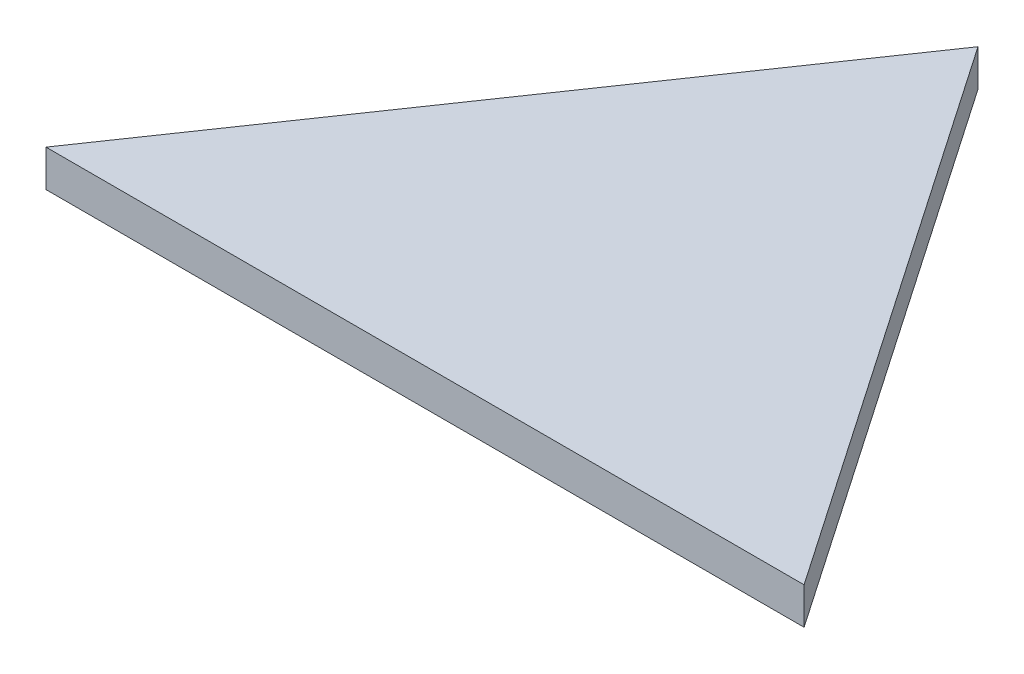
SolidWorks part; units mm, degrees
ref_plane "Front Plane" through (0, 0, 0) normal (0, 0, 1) x (1, 0, 0)
ref_plane "Top Plane" through (0, 0, 0) normal (0, 1, 0) x (1, 0, 0)
ref_plane "Right Plane" through (0, 0, 0) normal (1, 0, 0) x (0, 0, -1)
sketch "Sketch1" plane through (0, 0, 0) normal (0, 1, 0) x (1, 0, 0)
  line L0 (0, 0) -> (1854.0563, 0)
  line L1 (1854.0563, 0) -> (927.0281, 1352.3709)
  line L2 (927.0281, 1352.3709) -> (0, 0)
  dimension "D1" = 1639.6
  dimension "D3" = 68.86
extrude "Boss-Extrude1" add sketch "Sketch1" along normal blind 90
chamfer "Chamfer1" [suppressed] distance 60 angle 11
equation "\"D1@Boss-Extrude1\"=\"thicknes@Geodome.Assembly\""
equation "\"thickne\"=60"
equation "\"D1@Chamfer1\"=\"thickne\""
equation "\"Achanferangle\"=11"
equation "\"D2@Chamfer1\"=\"Achanferangle\""
